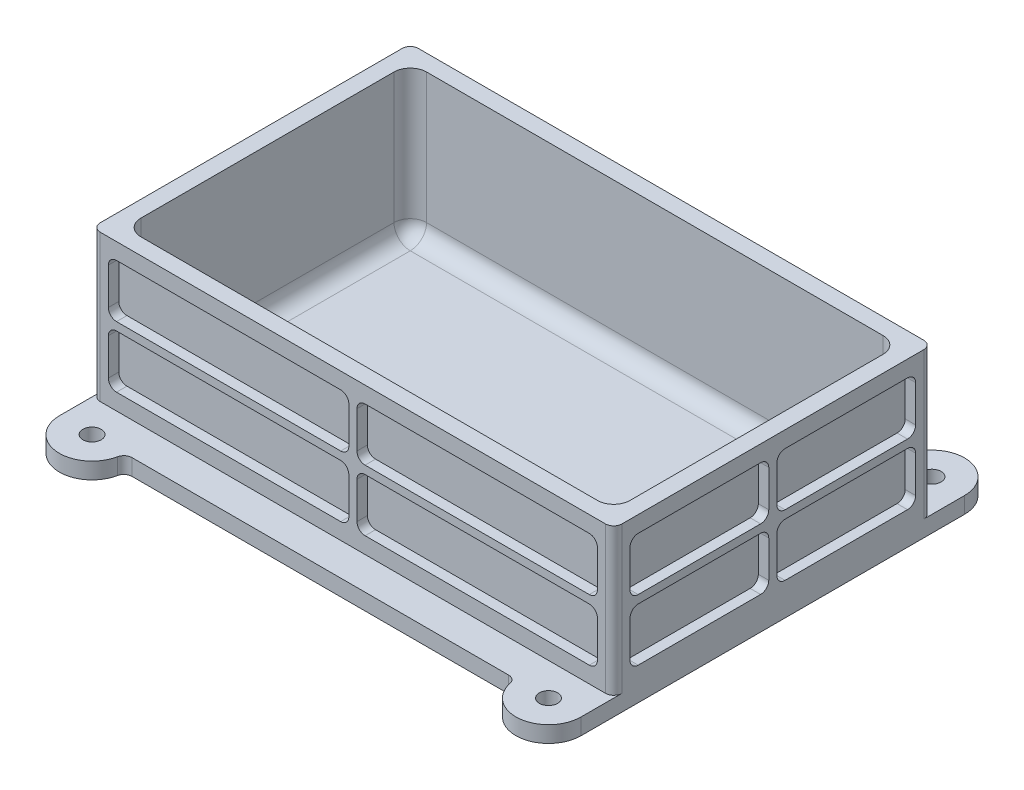
SolidWorks part; units mm, degrees
material "6061-T6 (SS)"
ref_plane "Front Plane" through (0, 0, 0) normal (0, 0, 1) x (1, 0, 0)
ref_plane "Top Plane" through (0, 0, 0) normal (0, 1, 0) x (1, 0, 0)
ref_plane "Right Plane" through (0, 0, 0) normal (1, 0, 0) x (0, 0, -1)
sketch "Sketch2" plane through (0, 0, 0) normal (0, 1, 0) x (1, 0, 0)
  line L1 (101.6, -61.976) -> (-101.6, -61.976)
  line L2 (101.6, -61.976) -> (101.6, 61.976)
  line L3 (101.6, 61.976) -> (-101.6, 61.976)
  line L4 (-101.6, -61.976) -> (-101.6, 61.976)
  line L5 (101.6, -61.976) -> (-101.6, 61.976) construction
  line L6 (101.6, 61.976) -> (-101.6, -61.976) construction
  point P0 (0, 0)
  dimension "D1" = 203.2
  dimension "D2" = 123.952
extrude "Main Block" add sketch "Sketch2" along normal blind 63.5
shell "Shell" thickness 6.35
sketch "Sketch6" plane through (0, 6.35, 0) normal (0, 1, 0) x (1, 0, 0)
  line L1 (-101.6, 61.976) -> (101.6, 61.976)
  line L2 (-101.6, 61.976) -> (-101.6, 87.376)
  line L3 (-101.6, 87.376) -> (101.6, 87.376)
  line L4 (101.6, 61.976) -> (101.6, 87.376)
  line L5 (-101.6, -61.976) -> (101.6, -61.976)
  line L6 (-101.6, -61.976) -> (-101.6, -87.376)
  line L7 (-101.6, -87.376) -> (101.6, -87.376)
  line L8 (101.6, -61.976) -> (101.6, -87.376)
  circle A0 centre (-88.9, 74.676) radius 3.5687
  circle A1 centre (88.9, 74.676) radius 3.5687
  circle A2 centre (88.9, -74.676) radius 3.5687
  circle A3 centre (-88.9, -74.676) radius 3.5687
  dimension "D5" = 7.1374
  dimension "D6" = 7.1374
  dimension "D7" = 7.1374
  dimension "D8" = 7.1374
  dimension "D1" = 25.4
  dimension "D2" = 203.2
  dimension "D3" = 25.4
  dimension "D4" = 203.2
  dimension "D9" = 12.7
  dimension "D10" = 12.7
  dimension "D11" = 12.7
  dimension "D12" = 12.7
  dimension "D13" = 12.7
  dimension "D14" = 12.7
  dimension "D15" = 12.7
  dimension "D16" = 12.7
extrude "Mounting Flanges" add sketch "Sketch6" against normal blind 6.35
sketch "Sketch7" plane through (0, 0, 61.976) normal (0, 0, 1) x (1, 0, 0)
  line L0 (-101.6, 63.5) -> (-101.6, 6.35) construction
  line L1 (-95.25, 57.15) -> (-1.5875, 57.15)
  line L2 (-95.25, 57.15) -> (-95.25, 36.5125)
  line L3 (-95.25, 12.7) -> (-1.5875, 12.7)
  line L4 (95.25, 57.15) -> (95.25, 36.5125)
  line L5 (-101.6, 63.5) -> (101.6, 63.5) construction
  line L6 (101.6, 63.5) -> (101.6, 6.35) construction
  line L7 (101.6, 6.35) -> (-101.6, 6.35) construction
  line L8 (-95.25, 34.925) -> (95.25, 34.925) construction
  line L9 (0, 57.15) -> (0, 12.7) construction
  line L10 (-1.5875, 33.3375) -> (-95.25, 33.3375)
  line L11 (-1.5875, 33.3375) -> (-1.5875, 12.7)
  line L12 (-95.25, 36.5125) -> (-1.5875, 36.5125)
  line L13 (-1.5875, 36.5125) -> (-1.5875, 57.15)
  line L14 (1.5875, 57.15) -> (1.5875, 36.5125)
  line L15 (1.5875, 36.5125) -> (95.25, 36.5125)
  line L16 (95.25, 33.3375) -> (1.5875, 33.3375)
  line L17 (1.5875, 33.3375) -> (1.5875, 12.7)
  line L18 (1.5875, 12.7) -> (95.25, 12.7)
  line L19 (1.5875, 57.15) -> (95.25, 57.15)
  line L20 (-95.25, 33.3375) -> (-95.25, 12.7)
  line L21 (95.25, 33.3375) -> (95.25, 12.7)
  dimension "D1" = 6.35
  dimension "D2" = 6.35
  dimension "D3" = 6.35
  dimension "D4" = 6.35
  dimension "D5" = 1.5875
  dimension "D6" = 95.25
  dimension "D7" = 3.175
  dimension "D8" = 3.175
  dimension "D9" = 1.5875
  dimension "D10" = 3.175
  dimension "D11" = 1.5875
  dimension "D12" = 3.175
  dimension "D13" = 1.5875
  dimension "D14" = 28.575
extrude "Long Side Ribbing" cut sketch "Sketch7" against normal blind 4.064
mirror "Mirror1" about plane through (0, 0, 0) normal (0, 0, 1) of "Long Side Ribbing"
sketch "Sketch8" plane through (101.6, 0, 0) normal (1, 0, 0) x (0, 0, -1)
  line L0 (-61.976, 63.5) -> (-61.976, 6.35) construction
  line L1 (-55.626, 57.15) -> (-1.5875, 57.15)
  line L2 (-55.626, 57.15) -> (-55.626, 36.5125)
  line L3 (-55.626, 12.7) -> (-1.5875, 12.7)
  line L4 (55.626, 57.15) -> (55.626, 36.5125)
  line L5 (61.976, 63.5) -> (61.976, 6.35) construction
  line L6 (61.976, 6.35) -> (87.376, 6.35) construction
  line L7 (-61.976, 63.5) -> (61.976, 63.5) construction
  line L8 (0, 12.7) -> (0, 57.15) construction
  line L9 (-55.626, 34.925) -> (55.626, 34.925) construction
  line L10 (-55.626, 33.3375) -> (-1.5875, 33.3375)
  line L11 (-1.5875, 33.3375) -> (-1.5875, 12.7)
  line L12 (-55.626, 36.5125) -> (-1.5875, 36.5125)
  line L13 (-1.5875, 36.5125) -> (-1.5875, 57.15)
  line L14 (1.5875, 57.15) -> (1.5875, 36.5125)
  line L15 (1.5875, 36.5125) -> (55.626, 36.5125)
  line L16 (55.626, 33.3375) -> (1.5875, 33.3375)
  line L17 (1.5875, 33.3375) -> (1.5875, 12.7)
  line L18 (1.5875, 57.15) -> (55.626, 57.15)
  line L19 (55.626, 33.3375) -> (55.626, 12.7)
  line L20 (1.5875, 12.7) -> (55.626, 12.7)
  line L21 (-55.626, 33.3375) -> (-55.626, 12.7)
  line L22 (61.976, 63.5) -> (61.976, 6.35) construction
  line L25 (61.976, 63.5) -> (-61.976, 63.5) construction
  dimension "D1" = 6.35
  dimension "D2" = 6.35
  dimension "D3" = 6.35
  dimension "D4" = 6.35
  dimension "D5" = 3.175
  dimension "D6" = 1.5875
  dimension "D7" = 3.175
  dimension "D8" = 1.5875
  dimension "D9" = 3.175
  dimension "D10" = 1.5875
  dimension "D11" = 3.175
  dimension "D12" = 61.976
  dimension "D13" = 28.575
extrude "Short Side Ribbing" cut sketch "Sketch8" against normal blind 4.064
mirror "Mirror2" about plane through (0, 0, 0) normal (1, 0, 0) of "Short Side Ribbing"
sketch "Sketch9" plane through (0, 6.35, 0) normal (0, 1, 0) x (1, 0, 0)
  line L0 (-101.6, -61.976) -> (-101.6, -87.376) construction
  line L1 (101.6, -87.376) -> (101.6, -61.976) construction
  line L2 (-76.2, -74.676) -> (76.2, -74.676)
  line L3 (-101.6, -74.676) -> (-114.1052, -74.676)
  line L4 (101.6, -74.676) -> (112.7667, -74.676)
  line L5 (112.7667, -74.676) -> (112.7667, -100.0512)
  line L6 (112.7667, -100.0512) -> (-114.1052, -100.0512)
  line L7 (-114.1052, -74.676) -> (-114.1052, -100.0512)
  arc A0 (-101.6, -74.676) -> (-76.2, -74.676) centre (-88.9, -74.676) ccw
  arc A1 (101.6, -74.676) -> (76.2, -74.676) centre (88.9, -74.676) cw
extrude "Cut-Extrude3" cut sketch "Sketch9" against normal through all
mirror "Mirror3" about plane through (0, 0, 0) normal (0, 0, 1) of "Cut-Extrude3"
fillet "External Fillets" radius 3.175 72 edges at (-101.6, 34.925, 61.976) (-101.6, 34.925, -61.976) (101.6, 34.925, -61.976) (101.6, 34.925, 61.976) (-99.568, 57.15, 55.626) (-99.568, 33.3375, 55.626) (-99.568, 36.5125, 55.626) (-99.568, 12.7, 55.626) (-99.568, 12.7, -1.5875) (-99.568, 33.3375, -1.5875) (-99.568, 36.5125, -1.5875) (-99.568, 57.15, -1.5875) (-99.568, 36.5125, 1.5875) (-99.568, 12.7, 1.5875) (-99.568, 33.3375, 1.5875) (-99.568, 57.15, 1.5875) (-99.568, 33.3375, -55.626) (-99.568, 57.15, -55.626) (-99.568, 12.7, -55.626) (-99.568, 36.5125, -55.626) (-95.25, 57.15, -59.944) (-95.25, 33.3375, -59.944) (-1.5875, 57.15, -59.944) (-1.5875, 33.3375, -59.944) (-1.5875, 12.7, -59.944) (-1.5875, 36.5125, -59.944) (1.5875, 57.15, -59.944) (1.5875, 33.3375, -59.944) (95.25, 33.3375, -59.944) (95.25, 57.15, -59.944) (95.25, 36.5125, -59.944) (95.25, 12.7, -59.944) (-95.25, 36.5125, -59.944) (-95.25, 12.7, -59.944) (1.5875, 12.7, -59.944) (1.5875, 36.5125, -59.944) (-76.2, 3.175, -74.676) (76.2, 3.175, -74.676) (76.2, 3.175, 74.676) (-76.2, 3.175, 74.676) (99.568, 57.15, -55.626) (99.568, 33.3375, -55.626) (99.568, 36.5125, -55.626) (99.568, 12.7, -55.626) (99.568, 12.7, 1.5875) (99.568, 33.3375, 1.5875) (99.568, 36.5125, 1.5875) (99.568, 57.15, 1.5875) (99.568, 12.7, -1.5875) (99.568, 33.3375, -1.5875) (99.568, 57.15, -1.5875) (99.568, 36.5125, -1.5875) (99.568, 12.7, 55.626) (99.568, 33.3375, 55.626) (99.568, 36.5125, 55.626) (99.568, 57.15, 55.626) (-95.25, 33.3375, 59.944) (-95.25, 12.7, 59.944) (-1.5875, 33.3375, 59.944) (-1.5875, 12.7, 59.944) (1.5875, 12.7, 59.944) (1.5875, 33.3375, 59.944) (95.25, 12.7, 59.944) (95.25, 33.3375, 59.944) (95.25, 57.15, 59.944) (95.25, 36.5125, 59.944) (1.5875, 57.15, 59.944) (1.5875, 36.5125, 59.944) (-1.5875, 36.5125, 59.944) (-95.25, 57.15, 59.944) (-95.25, 36.5125, 59.944) (-1.5875, 57.15, 59.944)
fillet "Internal Fillets" radius 6.35 8 edges at (95.25, 34.925, -55.626) (95.25, 34.925, 55.626) (-95.25, 34.925, 55.626) (-95.25, 34.925, -55.626) (95.25, 6.35, 0) (0, 6.35, 55.626) (0, 6.35, -55.626) (-95.25, 6.35, 0)
